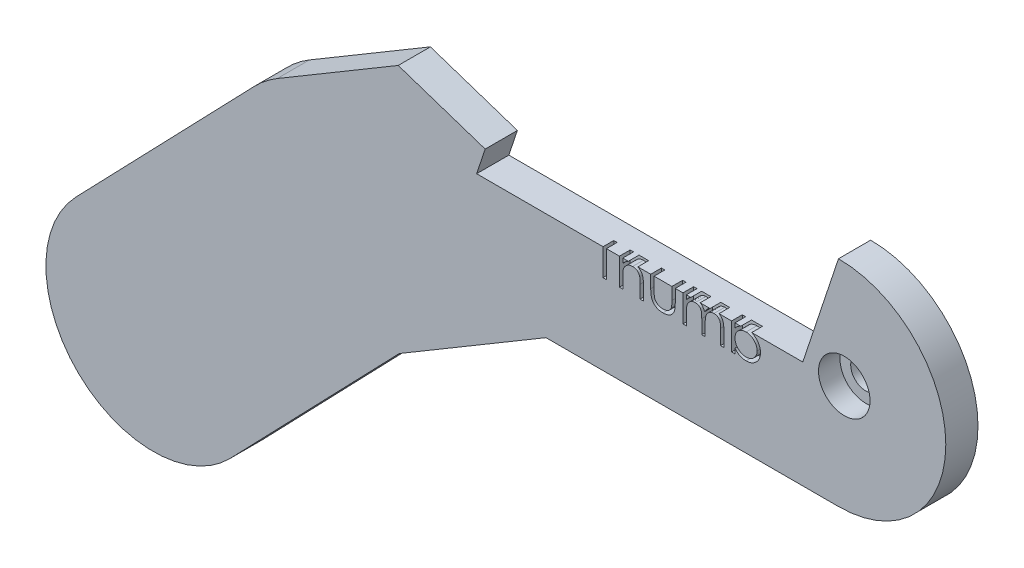
SolidWorks part; units mm, degrees
ref_plane "Front Plane" through (0, 0, 0) normal (0, 0, 1) x (1, 0, 0)
ref_plane "Top Plane" through (0, 0, 0) normal (0, 1, 0) x (1, 0, 0)
ref_plane "Right Plane" through (0, 0, 0) normal (1, 0, 0) x (0, 0, -1)
sketch "Sketch1" plane through (0, 0, 0) normal (0, 0, 1) x (1, 0, 0)
  line L0 (0, 0) -> (30, 0) construction
  line L2 (0, 10) -> (30, 10)
  line L3 (0, -10) -> (30, -10)
  arc A0 (0, 10) -> (0, -10) centre (0, 0) ccw
  arc A1 (30, -10) -> (30, 10) centre (30, 0) ccw
  point P5 (15, 0)
extrude "Boss-Extrude1" add sketch "Sketch1" along normal blind 3
sketch "Sketch2" plane through (0, 0, 0) normal (0, 0, 1) x (1, 0, 0)
  line L0 (0, 0) -> (-17.1984, -10.2085) construction
  line L2 (5.1043, -8.5992) -> (-12.0942, -18.8077)
  line L3 (-5.1043, 8.5992) -> (-22.3027, -1.6093)
  arc A0 (5.1043, -8.5992) -> (-5.1043, 8.5992) centre (0, 0) ccw
  arc A1 (-22.3027, -1.6093) -> (-12.0942, -18.8077) centre (-17.1984, -10.2085) ccw
  point P5 (-8.5992, -5.1043)
extrude "Boss-Extrude2" add sketch "Sketch2" along normal blind 3
sketch "Sketch3" plane through (0, 0, 0) normal (0, 0, 1) x (1, 0, 0)
  line L0 (-17.1984, -10.2085) -> (-33.8549, -27.4874) construction
  line L2 (-9.9989, -17.1487) -> (-26.6554, -34.4276)
  line L3 (-24.398, -3.2683) -> (-41.0545, -20.5472)
  arc A0 (-9.9989, -17.1487) -> (-24.398, -3.2683) centre (-17.1984, -10.2085) ccw
  arc A1 (-41.0545, -20.5472) -> (-26.6554, -34.4276) centre (-33.8549, -27.4874) ccw
  point P5 (-25.5267, -18.848)
extrude "Boss-Extrude4" add sketch "Sketch3" along normal blind 3
sketch "Sketch4" plane through (0, 0, 0) normal (0, 0, 1) x (1, 0, 0)
  circle A0 centre (30.5386, 0) radius 1.4
extrude "Cut-Extrude5" cut sketch "Sketch4" along normal blind 3
sketch "Sketch5" plane through (0, 0, 3) normal (0, 0, 1) x (1, 0, 0)
  circle A0 centre (30.5386, 0) radius 2.4
extrude "Cut-Extrude6" cut sketch "Sketch5" against normal blind 2
sketch "Sketch6" plane through (0, 0, 3) normal (0, 0, 1) x (1, 0, 0)
  text T0 "Thumb"
extrude "Cut-Extrude7" cut sketch "Sketch6" against normal blind 1
sketch "Sketch8" plane through (0, 0, 3) normal (0, 0, 1) x (1, 0, 0)
  line L0 (30, 10) -> (26.6724, 0)
  line L1 (30, 10) -> (-0.3898, 10)
  line L2 (26.6724, 0) -> (-3.7174, 0)
  line L3 (-0.3898, 10) -> (-3.7174, 0)
extrude "Cut-Extrude12" cut sketch "Sketch8" against normal through all both and the other way through all
sketch "Sketch12" plane through (0, 0, 3) normal (0, 0, 1) x (1, 0, 0)
  line L0 (-0.3924, 9.9923) -> (-2.9228, 2.3879)
  line L1 (-0.3924, 9.9923) -> (-3.7174, 0) construction
  line L2 (-2.9228, 2.3879) -> (-11.0259, 5.0843)
  line L3 (-5.1043, 8.5992) -> (-22.3027, -1.6093) construction
  line L4 (-11.0259, 5.0843) -> (-6.2401, 7.925)
  line L5 (-6.2401, 7.925) -> (-5.1043, 8.5992)
  line L6 (-5.1043, 8.5992) -> (-1.7999, 10.5606)
  line L7 (-1.7999, 10.5606) -> (-0.3924, 9.9923)
extrude "Cut-Extrude14" cut sketch "Sketch12" against normal blind 10
